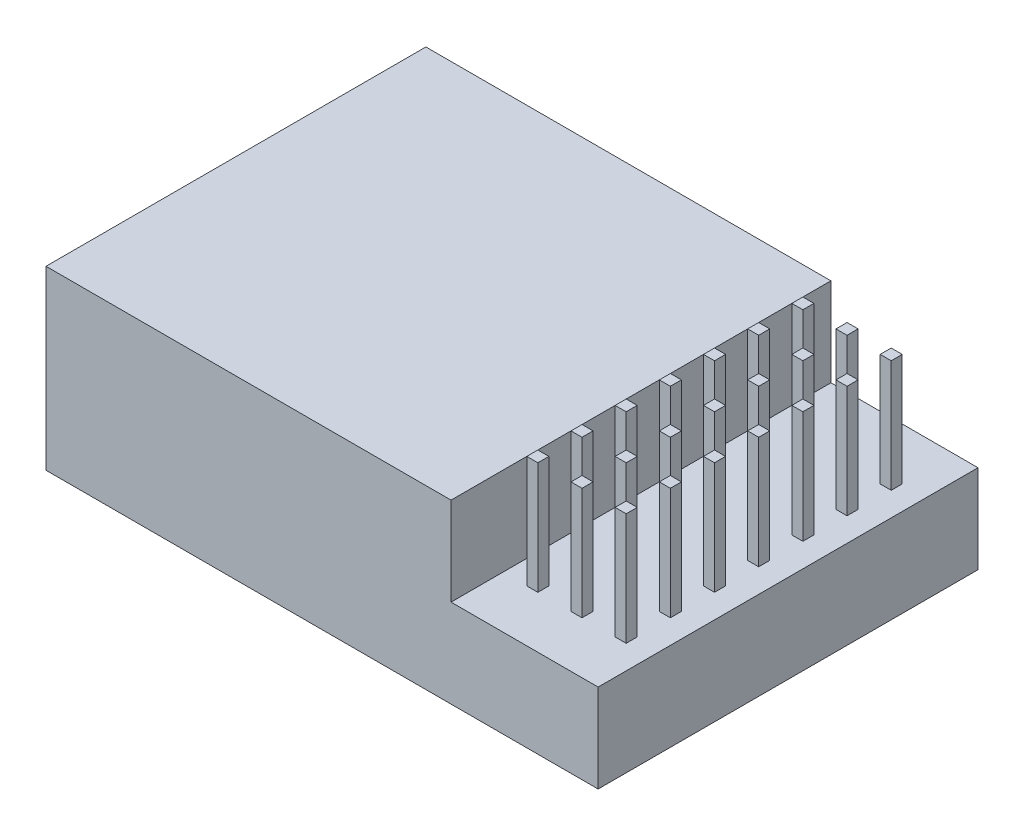
SolidWorks part; units mm, degrees
ref_plane "Front Plane" through (0, 0, 0) normal (0, 0, 1) x (1, 0, 0)
ref_plane "Top Plane" through (0, 0, 0) normal (0, 1, 0) x (1, 0, 0)
ref_plane "Right Plane" through (0, 0, 0) normal (1, 0, 0) x (0, 0, -1)
sketch "Sketch1" plane through (0, 0, 0) normal (0, 1, 0) x (1, 0, 0)
  line L0 (0, -55) -> (0, 55) construction
  line L1 (-15.875, 10.922) -> (15.875, 10.922)
  line L2 (-15.875, 10.922) -> (-15.875, -10.922)
  line L3 (-15.875, -10.922) -> (15.875, -10.922)
  line L4 (15.875, 10.922) -> (15.875, -10.922)
  line L5 (-55, 0) -> (55, 0) construction
  point P4 (0, 10.922)
  point P7 (-15.875, 0)
  dimension "D1" = 31.75
  dimension "D2" = 21.844
extrude "Boss-Extrude1" add sketch "Sketch1" along normal blind 10.16
sketch "Sketch2" plane through (0, 10.16, 0) normal (0, 1, 0) x (1, 0, 0)
  line L0 (-15.875, -10.922) -> (15.875, -10.922) construction
  line L1 (15.875, 10.922) -> (7.4168, 10.922)
  line L2 (15.875, 10.922) -> (15.875, -10.922)
  line L3 (15.875, -10.922) -> (7.4168, -10.922)
  line L4 (7.4168, 10.922) -> (7.4168, -10.922)
  dimension "D1" = 8.4582
extrude "Cut-Extrude1" cut sketch "Sketch2" against normal blind 5.08
sketch "Sketch3" plane through (0, 5.08, 0) normal (0, 1, 0) x (1, 0, 0)
  line L0 (11.6459, -1010.922) -> (11.6459, 48989.078) construction
  line L1 (13.8684, 0.3175) -> (14.5034, 0.3175)
  line L2 (13.8684, 0.3175) -> (13.8684, -0.3175)
  line L3 (13.8684, -0.3175) -> (14.5034, -0.3175)
  line L4 (14.5034, 0.3175) -> (14.5034, -0.3175)
  line L5 (11.3284, 0.3175) -> (11.9634, 0.3175)
  line L6 (11.3284, 0.3175) -> (11.3284, -0.3175)
  line L7 (11.3284, -0.3175) -> (11.9634, -0.3175)
  line L8 (11.9634, 0.3175) -> (11.9634, -0.3175)
  line L9 (8.7884, 0.3175) -> (9.4234, 0.3175)
  line L10 (8.7884, 0.3175) -> (8.7884, -0.3175)
  line L11 (8.7884, -0.3175) -> (9.4234, -0.3175)
  line L12 (9.4234, 0.3175) -> (9.4234, -0.3175)
  line L13 (7.4168, -10.922) -> (15.875, -10.922) construction
  line L14 (-1000, 0) -> (49000, 0) construction
  point P13 (11.6459, -0.3175)
  point P17 (11.6459, -10.922)
  point P19 (11.3284, 0)
  dimension "D1" = 2.54
  dimension "D2" = 2.54
  dimension "D3" = 0.635
extrude "Pins" add sketch "Sketch3" along normal blind 6.4516 separate body
pattern_linear "LPattern1" count 4 spacing 2.54 along (0, 0, -1) count 4 spacing 2.54 along (0, 0, 1) of "Pins"
